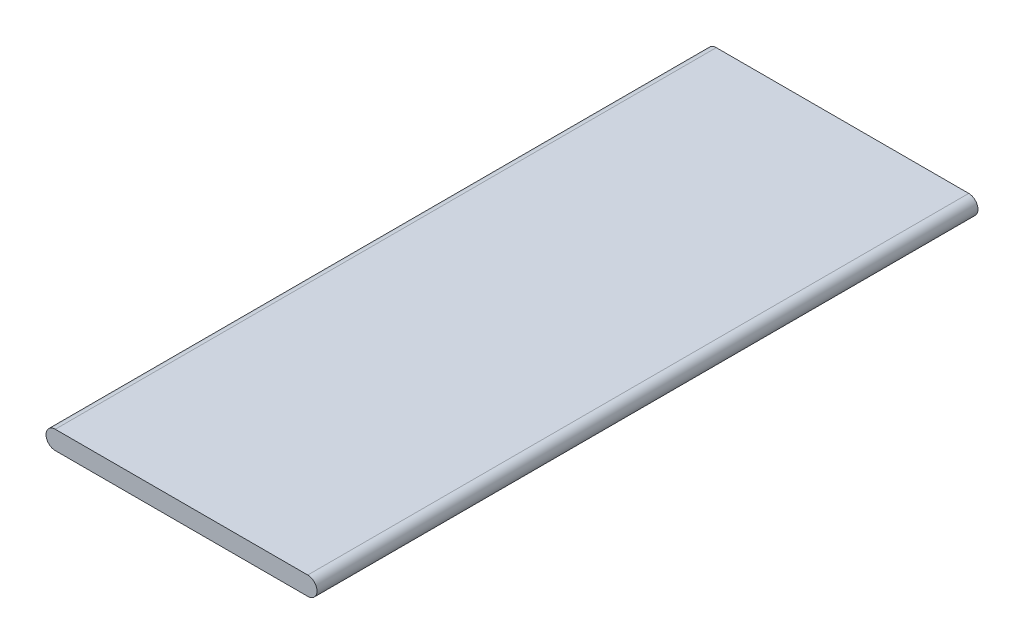
SolidWorks part; units mm, degrees
ref_plane "Front Plane" through (0, 0, 0) normal (0, 0, 1) x (1, 0, 0)
ref_plane "Top Plane" through (0, 0, 0) normal (0, 1, 0) x (1, 0, 0)
ref_plane "Right Plane" through (0, 0, 0) normal (1, 0, 0) x (0, 0, -1)
sketch "Sketch1" plane through (0, 0, 0) normal (0, 0, 1) x (1, 0, 0)
  line L0 (-5.4072, 0) -> (13.6928, 0) construction
  line L1 (-5.4072, 0.7) -> (13.6928, 0.7)
  line L2 (-5.4072, -0.7) -> (13.6928, -0.7)
  arc A0 (-5.4072, 0.7) -> (-5.4072, -0.7) centre (-5.4072, 0) ccw
  arc A1 (13.6928, -0.7) -> (13.6928, 0.7) centre (13.6928, 0) ccw
  point P3 (4.1428, 0)
extrude "Boss-Extrude1" add sketch "Sketch1" along normal blind 50
